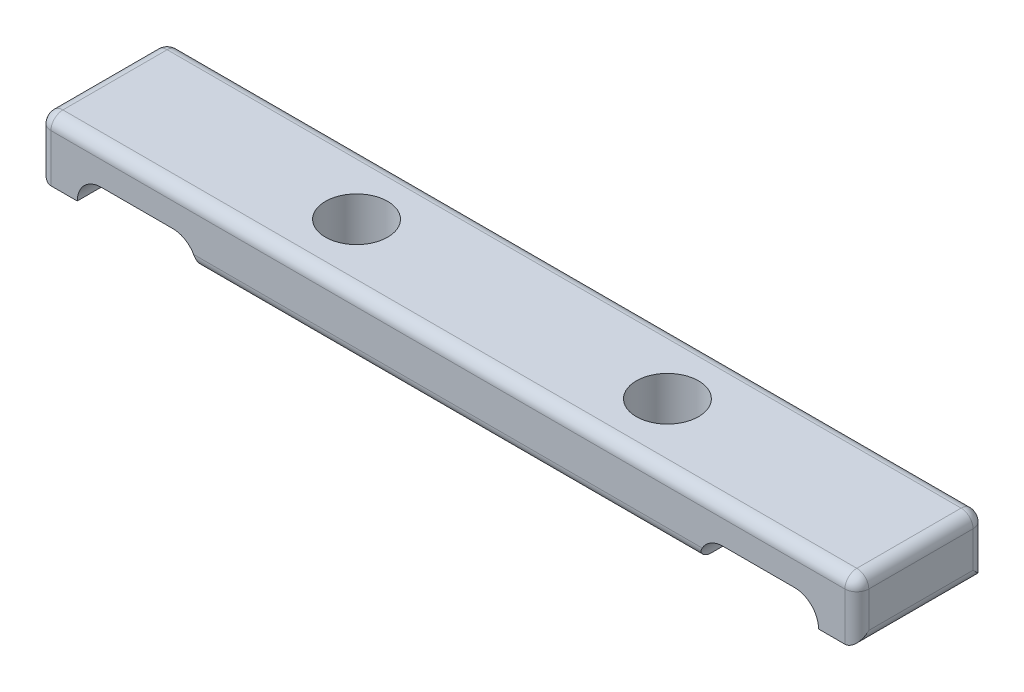
SolidWorks part; units mm, degrees
ref_plane "Front Plane" through (0, 0, 0) normal (0, 0, 1) x (1, 0, 0)
ref_plane "Top Plane" through (0, 0, 0) normal (0, 1, 0) x (1, 0, 0)
ref_plane "Right Plane" through (0, 0, 0) normal (1, 0, 0) x (0, 0, -1)
sketch "Sketch1" plane through (0, 0, 0) normal (0, 1, 0) x (1, 0, 0)
  line L1 (-34.2, 5.36) -> (34.2, 5.36)
  line L2 (-34.2, 5.36) -> (-34.2, -5.36)
  line L3 (-34.2, -5.36) -> (34.2, -5.36)
  line L4 (34.2, 5.36) -> (34.2, -5.36)
  line L5 (-34.2, 5.36) -> (34.2, -5.36) construction
  line L6 (-34.2, -5.36) -> (34.2, 5.36) construction
  point P0 (0, 0)
  dimension "D1" = 68.4
  dimension "D2" = 10.72
extrude "Boss-Extrude1" add sketch "Sketch1" along normal blind 5
sketch "Sketch2" plane through (0, 0, 5.36) normal (0, 0, 1) x (1, 0, 0)
  line L7 (0, 13.5015) -> (0, -7.642) construction
sketch "Sketch6" plane through (0, 0, 0) normal (0, 1, 0) x (1, 0, 0)
  line L0 (0, 11.1813) -> (0, -13.8345) construction
  line L1 (-36.7657, 0) -> (38.4713, 0) construction
  circle A0 centre (-13, 0) radius 2.6
  dimension "D1" = 5.2
  dimension "D2" = 13
extrude "Cut-Extrude3" cut sketch "Sketch6" along normal up to next
sketch "Sketch9" plane through (0, 0, 5.36) normal (0, 0, 1) x (1, 0, 0)
  line L0 (-34.2, 0) -> (34.2, 0) construction
  line L1 (0, 13.5015) -> (0, -7.642) construction
  line L2 (-29, 2) -> (-23, 2)
  arc A0 (-31, 0) -> (-29, 2) centre (-29, 0) cw
  arc A1 (-21, 0) -> (-23, 2) centre (-23, 0) ccw
  dimension "D1" = 2
  dimension "D2" = 2
  dimension "D3" = 23
  dimension "D4" = 29
extrude "Cut-Extrude4" cut sketch "Sketch9" against normal through all
mirror "Mirror4" about plane through (0, 0, 0) normal (1, 0, 0) of "Cut-Extrude4"
fillet "Fillet1" radius 1 1 edges at (-34.2, 5, 0)
fillet "Fillet2" radius 1 1 edges at (34.2, 5, 0)
mirror "Mirror5" about plane through (0, 0, 0) normal (1, 0, 0) of "Cut-Extrude3"
fillet "Fillet3" radius 1 14 edges at (-34.2, 2, 5.36) (-33.9071, 4.7071, 5.36) (34.2, 2, 5.36) (33.9071, 4.7071, 5.36) (34.2, 2, -5.36) (33.9071, 4.7071, -5.36) (-34.2, 2, -5.36) (-33.9071, 4.7071, -5.36) (34.2, 0, 0) (-34.2, 0, 0) (0, 5, 5.36) (0, 5, -5.36) (0, 0, 5.36) (0, 0, -5.36)
